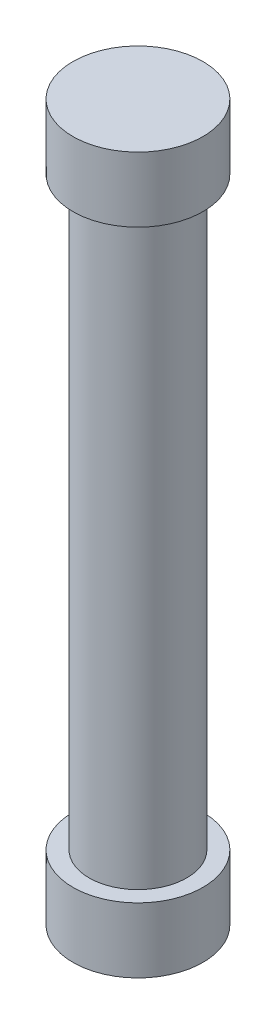
SolidWorks part; units mm, degrees
ref_plane "Front Plane" through (0, 0, 0) normal (0, 0, 1) x (1, 0, 0)
ref_plane "Top Plane" through (0, 0, 0) normal (0, 1, 0) x (1, 0, 0)
ref_plane "Right Plane" through (0, 0, 0) normal (1, 0, 0) x (0, 0, -1)
sketch "Sketch1" plane through (0, 0, 0) normal (0, 0, 1) x (1, 0, 0)
  line L0 (0, 3.9628) -> (0, -18.0372)
  line L1 (0, -18.0372) -> (-2, -18.0372)
  line L2 (-2, -18.0372) -> (-2, -16.0372)
  line L3 (-2, -16.0372) -> (-1.5, -16.0372)
  line L4 (-1.5, -16.0372) -> (-1.5, 1.9628)
  line L5 (-1.5, 1.9628) -> (-2, 1.9628)
  line L6 (-2, 1.9628) -> (-2, 3.9628)
  line L7 (-2, 3.9628) -> (0, 3.9628)
  dimension "D1" = 1.5
  dimension "D2" = 2
  dimension "D3" = 22
  dimension "D4" = 2
  dimension "D5" = 2
  dimension "D6" = 2
revolve "Revolve1" add sketch "Sketch1" angle 360 about L0
